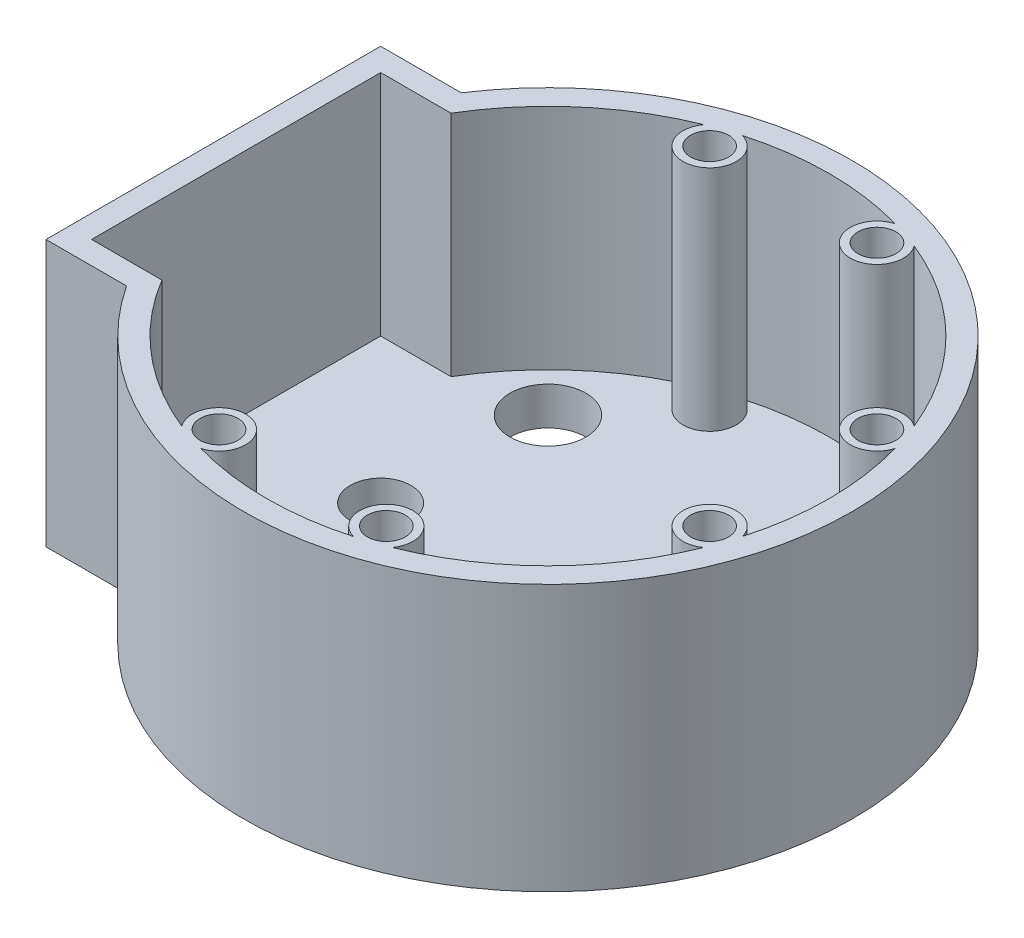
SolidWorks part; units mm, degrees
ref_plane "Front Plane" through (0, 0, 0) normal (0, 0, 1) x (1, 0, 0)
ref_plane "Top Plane" through (0, 0, 0) normal (0, 1, 0) x (1, 0, 0)
ref_plane "Right Plane" through (0, 0, 0) normal (1, 0, 0) x (0, 0, -1)
sketch "Sketch1" plane through (0, 0, 0) normal (0, 1, 0) x (1, 0, 0)
  line L0 (-0.4999, 1.2499) -> (-0.0033, 0)
  line L1 (-43.9951, 0) -> (-43.9951, -21.9976)
  line L2 (-43.9951, 0) -> (-43.9951, 21.9976)
  line L3 (-43.9951, 21.9976) -> (-33.4029, 21.9976)
  line L4 (-43.9951, -21.9976) -> (-33.4029, -21.9976)
  arc A14 (-33.4029, 21.9976) -> (-33.4029, -21.9976) centre (-0.0033, 0) cw
extrude "Boss-Extrude5" add sketch "Sketch1" along normal blind 5
sketch "Sketch3" plane through (0, 5, 0) normal (0, 1, 0) x (1, 0, 0)
  line L1 (-41, -19) -> (-41, 19.0042)
  line L2 (-41, 19.0042) -> (-31.749, 19.0042)
  line L3 (-41, -19) -> (-31.75, -19)
  arc A1 (-31.749, 19.0042) -> (-31.75, -19) centre (-0.0017, 0.0013) cw
  arc M1 (-33.4029, -21.9976) -> (-33.4029, 21.9976) centre (-0.0033, 0) ccw
  line M2 (-33.4029, 21.9976) -> (-43.9951, 21.9976)
  line M3 (-43.9951, 21.9976) -> (-43.9951, -21.9976)
  line M4 (-43.9951, -21.9976) -> (-33.4029, -21.9976)
  dimension "D1" = 37
extrude "Boss-Extrude6" add sketch "Sketch3" along normal blind 30 contours L2 A1 L3 L1 M4 M1 M2 M3
sketch "Sketch4" plane through (0, 5, 0) normal (0, 1, 0) x (1, 0, 0)
  circle A0 centre (-22, 0) radius 4
  circle A1 centre (-21, 21) radius 5
  circle A2 centre (21, 21) radius 5
  circle A3 centre (21, -21) radius 5
  circle A4 centre (-21, -21) radius 5
extrude "Cut-Extrude1" cut sketch "Sketch4" against normal blind 30
sketch "Sketch5" plane through (0, 5, 0) normal (0, 1, 0) x (1, 0, 0)
  circle A0 centre (-11, 32.25) radius 2.5
  circle A1 centre (11, 32.25) radius 2.5
  circle A2 centre (32.25, -11) radius 2.5
  circle A3 centre (32.25, 11) radius 2.5
  circle A4 centre (11, -32.25) radius 2.5
  circle A5 centre (-11, -32.25) radius 2.5
extrude "Cut-Extrude2" cut sketch "Sketch5" against normal blind 30
sketch "Sketch6" plane through (0, 5, 0) normal (0, 1, 0) x (1, 0, 0)
  circle A0 centre (-11, 32.25) radius 3.5
  circle A1 centre (11, 32.25) radius 3.5
  circle A2 centre (32.25, 11) radius 3.5
  circle A3 centre (32.25, -11) radius 3.5
  circle A4 centre (11, -32.25) radius 3.5
  circle A5 centre (-11, -32.25) radius 3.5
  circle M1 centre (-11, -32.25) radius 2.5
  circle M2 centre (11, 32.25) radius 2.5
  circle M3 centre (32.25, -11) radius 2.5
  circle M4 centre (32.25, 11) radius 2.5
  circle M5 centre (11, -32.25) radius 2.5
  circle M6 centre (-11, 32.25) radius 2.5
  arc M15 (-31.75, -19) -> (-31.749, 19.0042) centre (-0.0017, 0.0013) ccw
extrude "Boss-Extrude8" add sketch "Sketch6" along normal blind 30 contours A0 M15 M6 | A1 M15 M2 | A2 M15 M4 | A3 M15 M3 | A4 M15 M5 | A5 M15 M1
